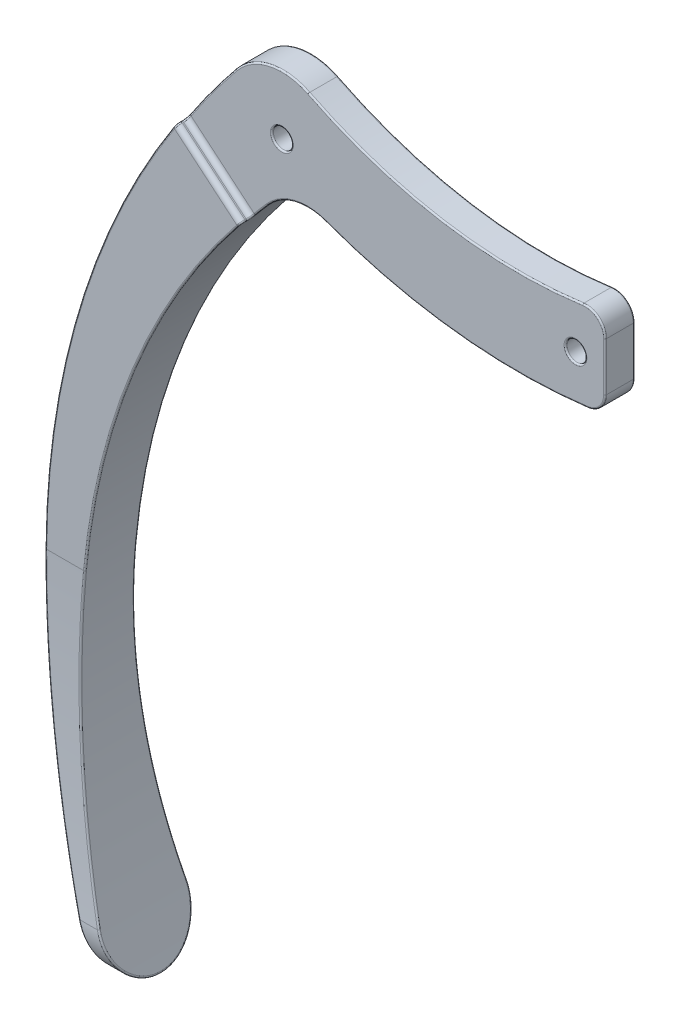
SolidWorks part; units mm, degrees
ref_plane "Front Plane" through (0, 0, 0) normal (0, 0, 1) x (1, 0, 0)
ref_plane "Top Plane" through (0, 0, 0) normal (0, 1, 0) x (1, 0, 0)
ref_plane "Right Plane" through (0, 0, 0) normal (1, 0, 0) x (0, 0, -1)
sketch "Sketch1" plane through (0, 0, 0) normal (0, 0, 1) x (1, 0, 0)
  line L0 (0, 4.5) -> (0, -4.5)
  line L1 (-46.08, -77.96) -> (-47.88, -77.96)
  arc A0 (0, -4.5) -> (-28.25, -1.6923) centre (-8.7418, 51.0666) cw
  arc A1 (0, 4.5) -> (-30, 8.7233) centre (-8.7418, 51.0666) cw
  arc A2 (-28.25, -1.6923) -> (-34.1239, -3.1783) centre (-30.1054, -6.7102) ccw
  arc A3 (-34.1239, -3.1783) -> (-46.08, -77.96) centre (19.2047, -50.0511) ccw
  arc A4 (-30, 8.7233) -> (-37.3384, 7.1573) centre (-32.692, 3.3611) ccw
  arc A5 (-37.3384, 7.1573) -> (-47.88, -77.96) centre (25.0008, -43.7747) ccw
  arc A6 (0, 0) -> (-28.862, 3.3236) centre (-8.7418, 51.0666) cw construction
  circle A7 centre (-32.692, 3.3611) radius 1
  circle A8 centre (-3, -0.4237) radius 1
  point P2 (0, 0)
  point P20 (0, 0)
  point P21 (0, 0)
  dimension "D2" = 47.38
  dimension "D3" = 56.25
  dimension "D6" = 5.35
  dimension "D7" = 71
  dimension "D9" = 6
  dimension "D10" = 80.5
  dimension "D13" = 2
  dimension "D1" = 9
  dimension "D4" = 28.25
  dimension "D5" = 30
  dimension "D8" = 77.96
  dimension "D11" = 47.88
  dimension "D12" = 1.8
  dimension "D14" = 3
sketch "Sketch2" plane through (0, 0, 0) normal (0, 0, 1) x (1, 0, 0)
  line L0 (0, 0) -> (0, -35) construction
  line L1 (0, -35) -> (-35.7046, -5.0403) construction
  line L2 (0, -4.5) -> (0, 4.5)
  line L3 (-47.88, -77.96) -> (-46.08, -77.96)
  line L5 (-47.88, -77.96) -> (-46.08, -77.96)
  line L6 (-35.7046, -5.0403) -> (-42.2576, 0.4583)
  arc A6 (-28.25, -1.6923) -> (0, -4.5) centre (-8.7418, 51.0666) ccw
  arc A7 (-28.25, -1.6923) -> (-34.1239, -3.1783) centre (-30.1054, -6.7102) ccw
  arc A8 (-34.1239, -3.1783) -> (-46.08, -77.96) centre (19.2047, -50.0511) ccw
  arc A9 (-37.3384, 7.1573) -> (-47.88, -77.96) centre (25.0008, -43.7747) ccw
  arc A10 (-30, 8.7233) -> (-37.3384, 7.1573) centre (-32.692, 3.3611) ccw
  arc A11 (-30, 8.7233) -> (0, 4.5) centre (-8.7418, 51.0666) ccw
  arc A14 (-35.7046, -5.0403) -> (-46.08, -77.96) centre (19.2047, -50.0511) ccw
  arc A15 (-42.2576, 0.4583) -> (-47.88, -77.96) centre (25.0008, -43.7747) ccw
  dimension "D4" = 35
  dimension "D5" = 50
  dimension "D1" = 0
extrude "Boss-Extrude1" add sketch "Sketch2" along normal mid plane 10
sketch "Sketch3" plane through (0, 0, 0) normal (1, 0, 0) x (0, 0, -1)
  line L3 (2.625, -43.3417) -> (2.625, 5.1583)
  line L4 (2.625, 5.1583) -> (-2.625, 5.1583) construction
  line L5 (-2.625, 5.1583) -> (-2.625, -43.3417)
  line L6 (-5, 0.4583) -> (5, 0.4583) construction
  line L7 (-2.625, 5.1583) -> (-38.723, 5.1583)
  line L8 (-38.723, 5.1583) -> (-38.723, -83.6269)
  line L9 (-38.723, -83.6269) -> (26.4559, -83.6269)
  line L10 (26.4559, -83.6269) -> (26.4559, 5.1583)
  line L11 (26.4559, 5.1583) -> (2.625, 5.1583)
  arc A3 (2.625, -43.3417) -> (4.4638, -72.272) centre (231.1292, -43.3417) ccw
  arc A4 (4.4638, -72.272) -> (-4.4638, -72.272) centre (0, -72.8417) cw
  arc A5 (-4.4638, -72.272) -> (-2.625, -43.3417) centre (-231.1292, -43.3417) ccw
  point P21 (0, 5.1583)
  dimension "D2" = 4.5
  dimension "D1" = 5.25
  dimension "D3" = 78
  dimension "D4" = 29.5
  dimension "D5" = 4.7
extrude "Cut-Extrude1" cut sketch "Sketch3" against normal through all
sketch "Sketch6" plane through (0, 0, 0) normal (0, 0, 1) x (1, 0, 0)
  line L0 (-42.2576, 0.4583) -> (-35.7046, -5.0403) construction
  line L1 (-42.2576, 0.4583) -> (-35.7046, -5.0403)
  line L4 (0, -4.5) -> (0, 4.5)
  line L5 (-47.88, -77.96) -> (-46.08, -77.96)
  line L6 (0, -4.5) -> (0, 4.5)
  line L7 (-47.88, -77.96) -> (-46.08, -77.96)
  circle A1 centre (-3, -0.4237) radius 1
  circle A2 centre (-3, -0.4237) radius 1
  circle A3 centre (-32.692, 3.3611) radius 1
  circle A4 centre (-32.692, 3.3611) radius 1
  arc A6 (-28.25, -1.6923) -> (0, -4.5) centre (-8.7418, 51.0666) ccw
  arc A7 (-28.25, -1.6923) -> (-34.1239, -3.1783) centre (-30.1054, -6.7102) ccw
  arc A8 (-34.1239, -3.1783) -> (-46.08, -77.96) centre (19.2047, -50.0511) ccw
  arc A9 (-37.3384, 7.1573) -> (-47.88, -77.96) centre (25.0008, -43.7747) ccw
  arc A10 (-30, 8.7233) -> (-37.3384, 7.1573) centre (-32.692, 3.3611) ccw
  arc A11 (-30, 8.7233) -> (0, 4.5) centre (-8.7418, 51.0666) ccw
  arc A12 (-28.25, -1.6923) -> (0, -4.5) centre (-8.7418, 51.0666) ccw
  arc A13 (-28.25, -1.6923) -> (-34.1239, -3.1783) centre (-30.1054, -6.7102) ccw
  arc A14 (-34.1239, -3.1783) -> (-35.7046, -5.0403) centre (19.2047, -50.0511) ccw
  arc A15 (-37.3384, 7.1573) -> (-42.2576, 0.4583) centre (25.0008, -43.7747) ccw
  arc A16 (-30, 8.7233) -> (-37.3384, 7.1573) centre (-32.692, 3.3611) ccw
  arc A17 (-30, 8.7233) -> (0, 4.5) centre (-8.7418, 51.0666) ccw
  dimension "D1" = 0
  dimension "D2" = 0
  dimension "D3" = 0
extrude "Boss-Extrude2" add sketch "Sketch6" along normal mid plane 3 contours A17 A16 A15 L1 A14 A13 A12 L6 A4 A2
fillet "Fillet1" radius 2 2 edges at (0, -4.5, 0) (0, 4.5, 0)
fillet "Fillet2" radius 0.5 4 edges at (-38.9811, -2.291, -2.625) (-38.9811, -2.291, -1.5) (-38.9811, -2.291, 1.5) (-38.9811, -2.291, 2.625)
fillet "Fillet3" radius 0.15 44 edges at (-42.1976, 0.5494, 1.6892) (-42.2576, 0.4583, 2.0625) (-42.3603, 0.3017, 2.5141) (-52.1279, -20.7223, 2.625) (-48.1722, -77.33, 0.3249) (-52.1279, -20.7223, -2.625) (-42.3174, 0.3672, -2.4357) (-42.2576, 0.4583, -2.0625) (-42.1544, 0.6148, -1.6108) (-35.635, -4.9556, -1.6877) (-35.7046, -5.0403, -2.0625) (-35.8233, -5.1856, -2.5154) (-46.5411, -23.2465, -2.625) (-51.794, -49.6234, -2.7114) (-46.3438, -77.3347, -0.2504) (-49.922, -66.2531, 3.7765) (-46.5411, -23.2465, 2.625) (-35.774, -5.1251, 2.4373) (-35.7046, -5.0403, 2.0625) (-35.5854, -4.8953, 1.6096) (-16.4849, 4.3236, -1.5) (-33.9442, 9.229, -1.5) (-39.7353, 4.0739, -1.5) (-34.7601, -3.9122, -1.5) (-31.4176, -1.5236, -1.5) (-15.1844, -4.8133, -1.5) (0, -0.307, -1.5) (-31.692, 3.3611, -1.5) (-2, -0.4237, -1.5) (-33.9442, 9.229, 1.5) (-39.7353, 4.0739, 1.5) (-34.7601, -3.9122, 1.5) (-31.4176, -1.5236, 1.5) (-15.1844, -4.8133, 1.5) (0, -0.307, 1.5) (-31.692, 3.3611, 1.5) (-2, -0.4237, 1.5) (-0.6859, 3.6566, -1.5) (-0.5005, -4.0863, -1.5) (-0.6859, 3.6566, 1.5) (-0.5005, -4.0863, 1.5) (-16.4849, 4.3236, 1.5)
